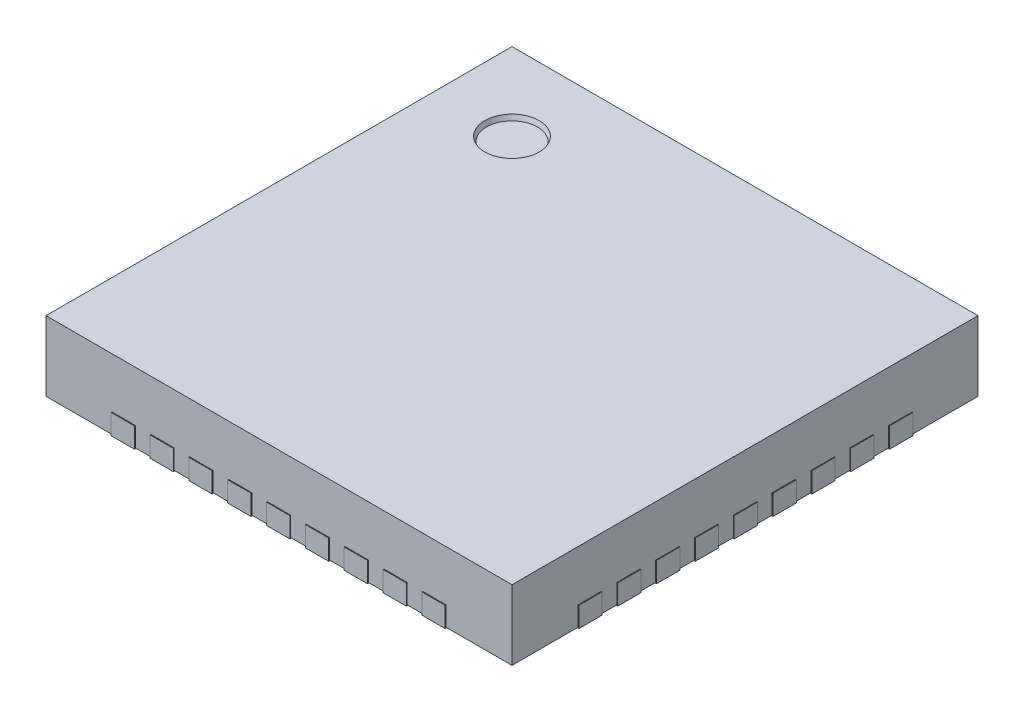
SolidWorks part; units mm, degrees
ref_plane "Front Plane" through (0, 0, 0) normal (0, 0, 1) x (1, 0, 0)
ref_plane "Top Plane" through (0, 0, 0) normal (0, 1, 0) x (1, 0, 0)
ref_plane "Right Plane" through (0, 0, 0) normal (1, 0, 0) x (0, 0, -1)
sketch "Sketch1" plane through (0, 0, 0) normal (0, 1, 0) x (1, 0, 0)
  line L1 (-3, 3) -> (3, 3)
  line L2 (-3, 3) -> (-3, -3)
  line L3 (-3, -3) -> (3, -3)
  line L4 (3, 3) -> (3, -3)
  line L5 (-3, 3) -> (3, -3) construction
  line L6 (-3, -3) -> (3, 3) construction
  point P0 (0, 0)
  dimension "D1" = 6
  dimension "D2" = 6
extrude "Boss-Extrude1" add sketch "Sketch1" along normal blind 0.9
sketch "Sketch3" plane through (0, 0.9, 0) normal (0, 1, 0) x (1, 0, 0)
  line L0 (3, 3) -> (-3, 3) construction
  line L1 (-3, 3) -> (-3, -3) construction
  circle A0 centre (-2, 2) radius 0.35
  dimension "D1" = 0.7
  dimension "D2" = 1
  dimension "D3" = 1
extrude "Cut-Extrude1" cut sketch "Sketch3" against normal blind 0.06 draft 20
sketch "Sketch2" plane through (0, 0, 0) normal (0, -1, 0) x (1, 0, 0)
  line L0 (0, 0) -> (0, 2.36) construction
  line L1 (-0.15, 3.01) -> (0.15, 3.01)
  line L2 (-0.15, 3.01) -> (-0.15, 2.36)
  line L3 (-0.15, 2.36) -> (0.15, 2.36)
  line L4 (0.15, 3.01) -> (0.15, 2.36)
  line L5 (-3, 3) -> (3, 3) construction
  line L6 (-0.15, 2.4844) -> (0.15, 2.4844) construction
  arc A0 (-0.15, 2.4844) -> (0.15, 2.4844) centre (0, 2.5126) ccw
  point P4 (0, 2.36)
  point P11 (0.15, 2.685)
  line M7 (3, 3) -> (-3, 3)
  dimension "D1" = 0.65
  dimension "D2" = 0.01
  dimension "D3" = 0.3
  dimension "D4" = 2.685
extrude "middle_pin" add sketch "Sketch2" along normal blind 0.01 and the other way blind 0.25 contours A0 L4 L2 M7 | L4 L1 L2 M7
pattern_linear "LPattern1" count 5 spacing 0.5 along (-1, 0, 0) count 5 spacing 0.5 along (1, 0, 0) of "middle_pin"
mirror "Mirror1" about plane through (0, 0, 0) normal (0, 0, 1) of "LPattern1", "middle_pin"
sketch "Sketch4" plane through (0, 0, 0) normal (0, -1, 0) x (1, 0, 0)
  point P0 (0, 0)
pattern_circular "CirPattern1" count 4 every 90 about axis through (0, 0, 0) along (0, 1, 0) skipping 2 of "LPattern1", "middle_pin"
sketch "Sketch5" plane through (0, 0, 0) normal (0, -1, 0) x (1, 0, 0)
  line L1 (-2.075, 2.075) -> (2.075, 2.075)
  line L2 (-2.075, 2.075) -> (-2.075, -2.075)
  line L3 (-2.075, -2.075) -> (2.075, -2.075)
  line L4 (2.075, 2.075) -> (2.075, -2.075)
  line L5 (-2.075, 2.075) -> (2.075, -2.075) construction
  line L6 (-2.075, -2.075) -> (2.075, 2.075) construction
  circle A0 centre (-2.075, -2.075) radius 0.192
  point P0 (0, 0)
  dimension "D1" = 4.15
  dimension "D2" = 4.15
extrude "Boss-Extrude3" add sketch "Sketch5" along normal blind 0.01 contours A0 L3 L4 L1 L2
equation "\"pin_width\"= 0.25"
equation "\"pin_length\"= 0.65"
equation "\"pin_spacing\"= 0.5"
equation "\"number of pins\"= 36"
equation "\"pin_per_side\"= \"number of pins\" / 4"
equation "\"D1@Sketch2\"= \"pin_length\""
equation "\"body_dimension\"= 6"
equation "\"D1@Sketch1\"= \"body_dimension\""
equation "\"D2@Sketch1\"= \"body_dimension\""
